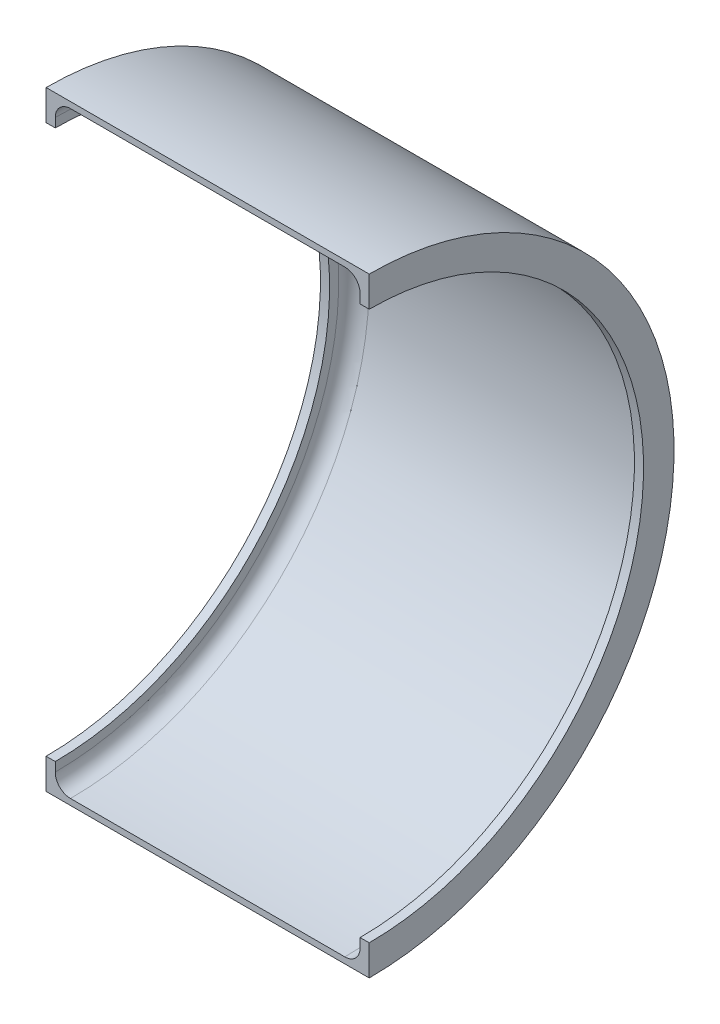
SolidWorks part; units mm, degrees
ref_plane "正面" through (0, 0, 0) normal (0, 0, 1) x (1, 0, 0)
ref_plane "平面" through (0, 0, 0) normal (0, 1, 0) x (1, 0, 0)
ref_plane "右側面" through (0, 0, 0) normal (1, 0, 0) x (0, 0, -1)
sketch "ｽｹｯﾁ1" plane through (0, 0, 0) normal (0, 0, 1) x (1, 0, 0)
  line L1 (-50, 100) -> (50, 100)
  line L2 (-50, 100) -> (-50, 98)
  line L3 (-50, 98) -> (50, 98)
  line L4 (50, 100) -> (50, 98)
  line L5 (-50, 100) -> (50, 98) construction
  line L6 (-50, 98) -> (50, 100) construction
  point P0 (0, 99)
  dimension "D1" = 100
  dimension "D2" = 100
  dimension "D3" = 2
sketch "ｽｹｯﾁ2" plane through (0, 0, 0) normal (0, 0, 1) x (1, 0, 0)
  line L0 (-50, 0) -> (50, 0)
  point P4 (0, 0)
  dimension "D1" = 100
revolve "回転1" add sketch "ｽｹｯﾁ1" angle 180 about L0
sketch "ｽｹｯﾁ3" plane through (0, 0, 0) normal (0, 0, 1) x (1, 0, 0)
  line L1 (50, 100) -> (53, 100)
  line L2 (50, 100) -> (50, 90)
  line L3 (50, 90) -> (53, 90)
  line L4 (53, 100) -> (53, 90)
  dimension "D1" = 10
  dimension "D2" = 3
revolve "回転2" add sketch "ｽｹｯﾁ3" angle 180 about L0
fillet "ﾌｨﾚｯﾄ1" radius 5 1 edges at (50, 0, -98)
mirror "ﾐﾗｰ1" about plane through (0, 0, 0) normal (1, 0, 0) of "ﾌｨﾚｯﾄ1", "回転2"
